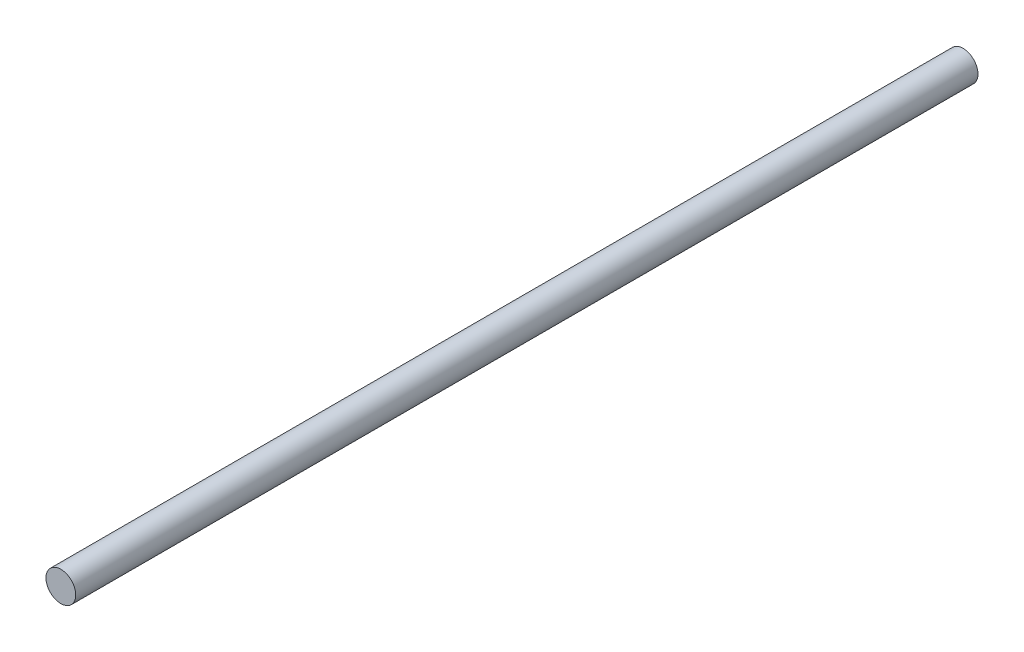
SolidWorks part; units mm, degrees
ref_plane "Front Plane" through (0, 0, 0) normal (0, 0, 1) x (1, 0, 0)
ref_plane "Top Plane" through (0, 0, 0) normal (0, 1, 0) x (1, 0, 0)
ref_plane "Right Plane" through (0, 0, 0) normal (1, 0, 0) x (0, 0, -1)
sketch "Sketch1" plane through (0, 0, 0) normal (0, 0, 1) x (1, 0, 0)
  circle A0 centre (0, 0) radius 5
extrude "Boss-Extrude1" add sketch "Sketch1" along normal blind 303
